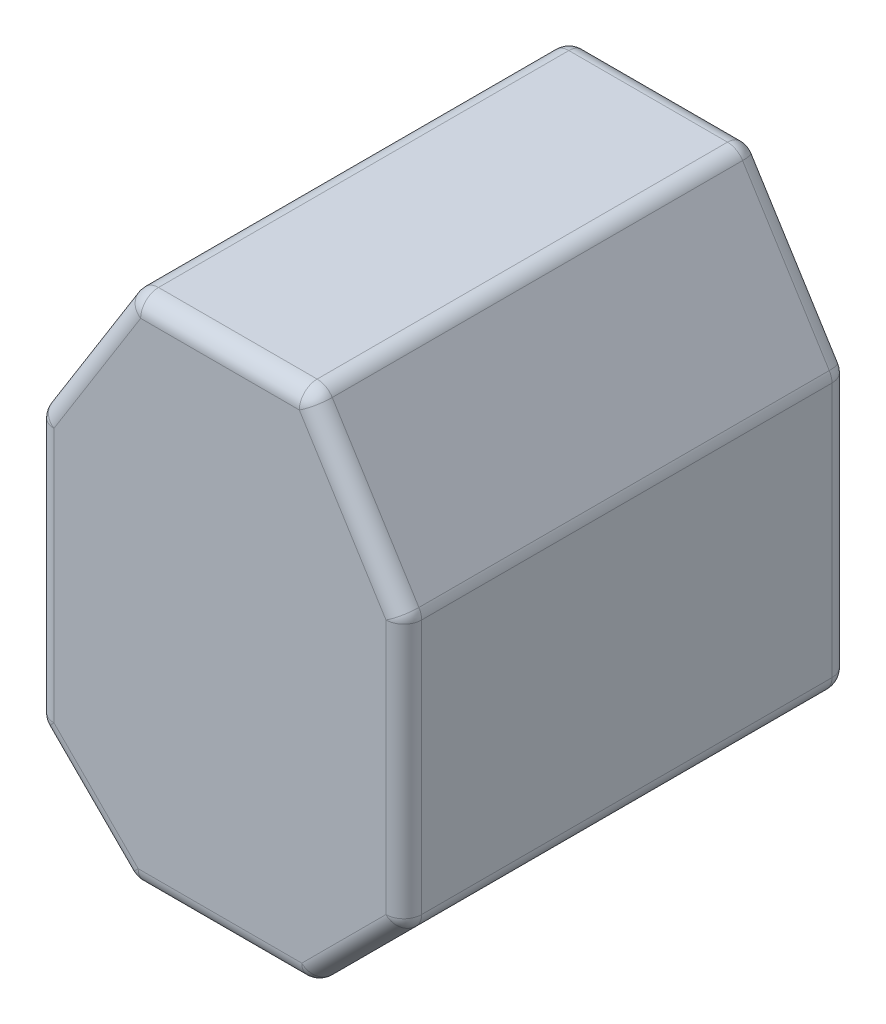
SolidWorks part; units mm, degrees
ref_plane "Front Plane" through (0, 0, 0) normal (0, 0, 1) x (1, 0, 0)
ref_plane "Top Plane" through (0, 0, 0) normal (0, 1, 0) x (1, 0, 0)
ref_plane "Right Plane" through (0, 0, 0) normal (1, 0, 0) x (0, 0, -1)
sketch "Sketch1" plane through (0, 0, 0) normal (0, 0, 1) x (1, 0, 0)
  line L0 (0, 0) -> (-20, 0)
  line L7 (-20, 0) -> (-30.6066, -16.9558)
  line L8 (-30.6066, -16.9558) -> (-30.6066, -46.9558)
  line L9 (-30.6066, -46.9558) -> (-20, -57.5624)
  line L10 (-20, -57.5624) -> (0, -57.5624)
  line L11 (0, -57.5624) -> (10.6066, -46.9558)
  line L12 (10.6066, -46.9558) -> (10.6066, -16.9558)
  line L13 (10.6066, -16.9558) -> (0, 0)
  dimension "D1" = 30
  dimension "D2" = 30
  dimension "D3" = 20
  dimension "D4" = 20
  dimension "D5" = 20
  dimension "D6" = 20
  dimension "D7" = 15
  dimension "D8" = 15
extrude "Boss-Extrude1" add sketch "Sketch1" along normal blind 50
fillet "Fillet1" radius 2 24 edges at (5.3033, -8.4779, 0) (-10, 0, 0) (-25.3033, -8.4779, 0) (-30.6066, -31.9558, 0) (-25.3033, -52.2591, 0) (-10, -57.5624, 0) (5.3033, -52.2591, 0) (10.6066, -31.9558, 0) (5.3033, -8.4779, 50) (-10, 0, 50) (-25.3033, -8.4779, 50) (-30.6066, -31.9558, 50) (-25.3033, -52.2591, 50) (-10, -57.5624, 50) (5.3033, -52.2591, 50) (10.6066, -31.9558, 50) (10.6066, -16.9558, 25) (10.6066, -46.9558, 25) (-30.6066, -16.9558, 25) (-20, 0, 25) (0, 0, 25) (0, -57.5624, 25) (-20, -57.5624, 25) (-30.6066, -46.9558, 25)
